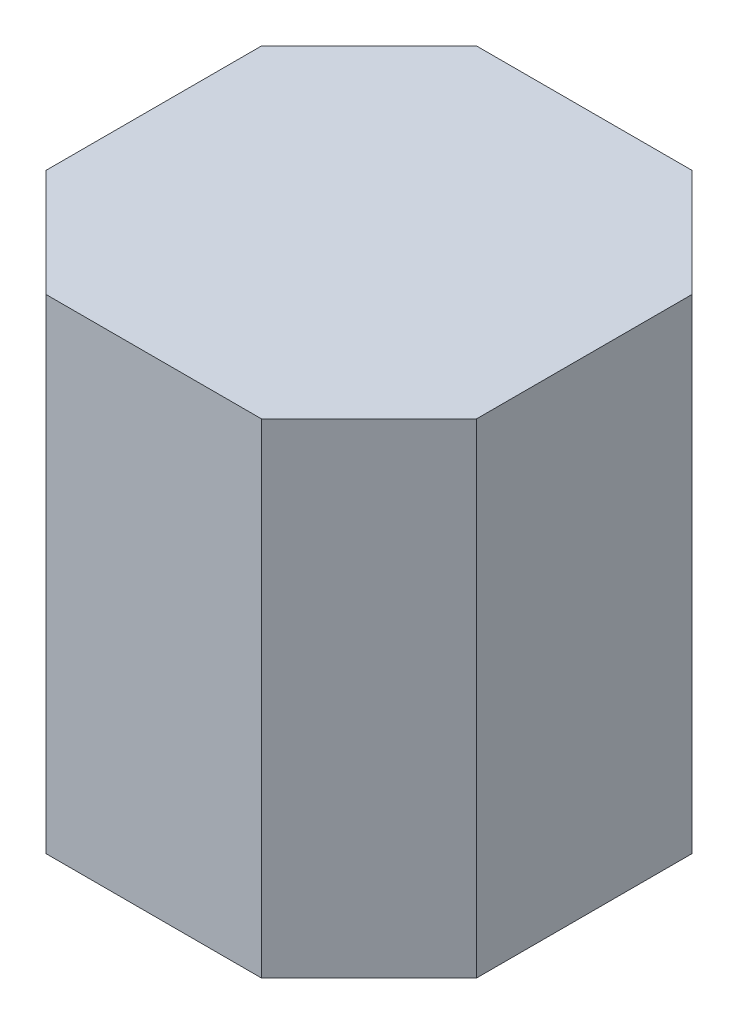
SolidWorks part; units mm, degrees
ref_plane "Plan de face" through (0, 0, 0) normal (0, 0, 1) x (1, 0, 0)
ref_plane "Plan de dessus" through (0, 0, 0) normal (0, 1, 0) x (1, 0, 0)
ref_plane "Plan de droite" through (0, 0, 0) normal (1, 0, 0) x (0, 0, -1)
sketch "Esquisse2" plane through (0, 0, 0) normal (0, 1, 0) x (1, 0, 0)
  line L0 (0, 40) -> (40, 40) construction
  line L1 (40, 40) -> (40, -40) construction
  line L2 (40, -40) -> (-40, -40) construction
  line L3 (-40, -40) -> (-40, 40) construction
  line L4 (-40, 40) -> (0, 40) construction
  line L5 (-40, 40) -> (-40, 20) construction
  line L6 (-40, 20) -> (-20, 20) construction
  line L7 (-20, 20) -> (-20, 40) construction
  line L8 (-20, 40) -> (-40, 20)
  line L9 (0, -55) -> (0, 55) construction
  line L10 (20, 40) -> (40, 20)
  line L11 (-55, 0) -> (55, 0) construction
  line L12 (20, -40) -> (40, -20)
  line L13 (-20, -40) -> (-40, -20)
  line L14 (-40, -20) -> (-40, 20)
  line L15 (-20, 40) -> (20, 40)
  line L16 (40, 20) -> (40, -20)
  line L17 (20, -40) -> (-20, -40)
  circle A0 centre (0, 0) radius 40 construction
  dimension "D1" = 80
  dimension "D2" = 80
extrude "Boss.-Extru.1" add sketch "Esquisse2" along normal blind 90
sketch "Esquisse3" plane through (0, 0, 0) normal (0, -1, 0) x (1, 0, 0)
  circle A0 centre (0, 0) radius 25
extrude "Enlèv. mat.-Extru.1" cut sketch "Esquisse3" against normal blind 70
sketch "Esquisse5" plane through (0, 0, 0) normal (0, -1, 0) x (1, 0, 0)
  line L0 (0, 0) -> (0, 32) construction
  line L1 (0, 0) -> (32, 0) construction
  line L2 (0, 0) -> (0, -32) construction
  line L3 (0, 0) -> (-32, 0) construction
  circle A0 centre (-32, 0) radius 2
  circle A1 centre (0, -32) radius 2
  circle A3 centre (32, 0) radius 2
  circle A4 centre (0, 32) radius 2
extrude "Enlèv. mat.-Extru.3" cut sketch "Esquisse5" against normal blind 15
